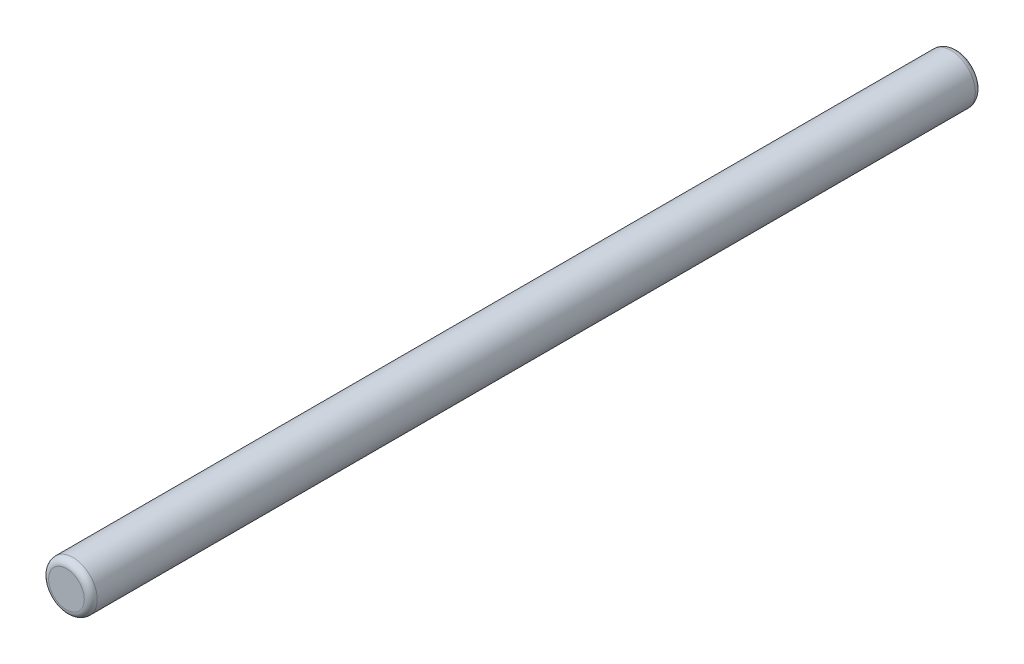
SolidWorks part; units mm, degrees
ref_plane "Front Plane" through (0, 0, 0) normal (0, 0, 1) x (1, 0, 0)
ref_plane "Top Plane" through (0, 0, 0) normal (0, 1, 0) x (1, 0, 0)
ref_plane "Right Plane" through (0, 0, 0) normal (1, 0, 0) x (0, 0, -1)
sketch "Sketch1" plane through (0, 0, 0) normal (0, 0, 1) x (1, 0, 0)
  circle A0 centre (0, 0) radius 7.5
  dimension "D1" = 15
extrude "Boss-Extrude1" add sketch "Sketch1" along normal mid plane 275
fillet "Fillet1" radius 2 2 edges at (7.5, 0, -137.5) (7.5, 0, 137.5)
